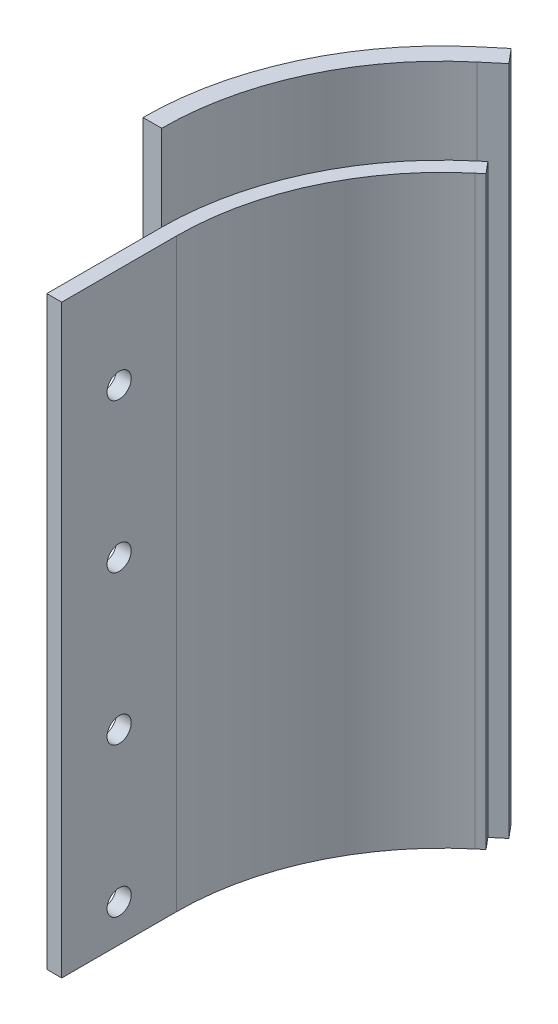
SolidWorks part; units mm, degrees
material "Custom Plastic"
ref_plane "Front Plane" through (0, 0, 0) normal (0, 0, 1) x (1, 0, 0)
ref_plane "Top Plane" through (0, 0, 0) normal (0, 1, 0) x (1, 0, 0)
ref_plane "Right Plane" through (0, 0, 0) normal (1, 0, 0) x (0, 0, -1)
sketch "Sketch1" plane through (0, 0, 0) normal (0, 1, 0) x (1, 0, 0)
  line L0 (0, 0) -> (77.7862, 0) construction
  line L1 (77.7862, 0) -> (77.7862, 50) construction
  line L2 (0, 0) -> (0, -10) construction
  line L3 (23.3154, 50) -> (-36.2723, 0) construction
  line L4 (10, 0) -> (-10, 0)
  line L5 (29.7433, 42.3396) -> (16.8875, 57.6604)
  arc A0 (0, 0) -> (23.3154, 50) centre (65.2704, 0) cw construction
  arc A1 (10, 0) -> (29.7433, 42.3396) centre (65.2704, 0) cw
  arc A2 (-10, 0) -> (16.8875, 57.6604) centre (65.2704, 0) cw
  circle A3 centre (0.7706, 10) radius 2.6
  circle A4 centre (6.1153, 27.5844) radius 2.6
  circle A5 centre (16.1503, 42.9818) radius 2.6
  circle A7 centre (30.0798, 54.9713) radius 2.6 [skipped]
  point P24 (65.2704, 0)
  dimension "D6" = 5.2
  dimension "D9" = 10
  dimension "D1" = 10
  dimension "D2" = 40
  dimension "D3" = 50
  dimension "D7" = 10
  dimension "D8" = 4
  dimension "D4" = 10
  dimension "D5" = 10
extrude "Boss-Extrude1" add sketch "Sketch1" along normal blind 20
sketch "Sketch2" plane through (0, 20, 0) normal (0, 1, 0) x (1, 0, 0)
  line L0 (16.8875, 57.6604) -> (29.7433, 42.3396)
  line L1 (16.8875, 57.6604) -> (21.5604, 61.5814)
  line L2 (29.7433, 42.3396) -> (34.4161, 46.2606)
  line L3 (21.5604, 61.5814) -> (34.4161, 46.2606)
  dimension "D1" = 6.1
extrude "Boss-Extrude2" add sketch "Sketch2" against normal up to surface (20 mm away) up to face at (0.7706, 0, -7.4)
sketch "Sketch3" plane through (0, 20, 0) normal (0, 1, 0) x (1, 0, 0)
  line L5 (21.5604, 61.5814) -> (16.8875, 57.6604) construction
  line L6 (18.3464, 65.4117) -> (13.6736, 61.4907)
  line L7 (18.3464, 65.4117) -> (13.6736, 61.4907)
  line L8 (21.5604, 61.5814) -> (16.8875, 57.6604)
  line L9 (-15, 0) -> (-10, 0)
  line L10 (18.3464, 65.4117) -> (21.5604, 61.5814)
  arc A4 (16.8875, 57.6604) -> (-10, 0) centre (65.2704, 0) ccw construction
  arc A5 (13.6736, 61.4907) -> (-15, 0) centre (65.2704, 0) ccw
  arc A6 (13.6736, 61.4907) -> (-15, 0) centre (65.2704, 0) ccw
  arc A7 (16.8875, 57.6604) -> (-10, 0) centre (65.2704, 0) ccw
  dimension "D1" = 5
extrude "Boss-Extrude3" add sketch "Sketch3" along normal blind 180 separate body
sketch "Sketch4" plane through (0, 20, 0) normal (0, 1, 0) x (1, 0, 0)
  line L4 (29.7433, 42.3396) -> (34.4161, 46.2606)
  line L5 (34.4161, 46.2606) -> (21.5604, 61.5814)
  line L6 (21.5604, 61.5814) -> (16.8875, 57.6604)
  line L7 (-10, 0) -> (10, 0)
  line L8 (29.7433, 42.3396) -> (34.4161, 46.2606)
  line L9 (34.4161, 46.2606) -> (21.5604, 61.5814)
  line L10 (21.5604, 61.5814) -> (16.8875, 57.6604)
  line L11 (-10, 0) -> (10, 0)
  arc A2 (29.7433, 42.3396) -> (10, 0) centre (65.2704, 0) ccw
  arc A3 (16.8875, 57.6604) -> (-10, 0) centre (65.2704, 0) ccw
  arc A4 (29.7433, 42.3396) -> (10, 0) centre (65.2704, 0) ccw
  arc A5 (16.8875, 57.6604) -> (-10, 0) centre (65.2704, 0) ccw
  dimension "D1" = 0
extrude "Cut-Extrude1" cut sketch "Sketch4" against normal through all
sketch "Sketch6" plane through (0, 200, 0) normal (0, 1, 0) x (1, 0, 0)
  line L0 (16.8875, 57.6604) -> (21.5604, 61.5814) construction
  line L1 (16.8875, 57.6604) -> (21.5604, 61.5814)
  line L2 (-10, 0) -> (-10, -30.7992)
  line L3 (-10, -30.7992) -> (-6, -30.7992)
  line L4 (-6, -30.7992) -> (-6, 0)
  line L5 (19.4587, 54.5963) -> (24.1315, 58.5173)
  line L6 (21.5604, 61.5814) -> (24.1315, 58.5173)
  arc A0 (16.8875, 57.6604) -> (-10, 0) centre (65.2704, 0) ccw construction
  arc A1 (16.8875, 57.6604) -> (-10, 0) centre (65.2704, 0) ccw
  arc A2 (19.4587, 54.5963) -> (-6, 0) centre (65.2704, 0) ccw
  dimension "D1" = 4
extrude "Boss-Extrude4" add sketch "Sketch6" against normal up to surface (157 mm away) from offset 23 up to face at (5.3767, 20, -42.0505) offset against normal yes
sketch "Sketch7" plane through (-10, 0, 0) normal (-1, 0, 0) x (0, 0, 1)
  line L0 (15.3996, 177) -> (15.3996, 20) construction
  line L1 (0, 177) -> (30.7992, 177) construction
  line L2 (30.7992, 20) -> (0, 20) construction
  circle A0 centre (15.3996, 30) radius 3.25
  circle A1 centre (15.3996, 70) radius 3.25
  circle A2 centre (15.3996, 110) radius 3.25
  circle A3 centre (15.3996, 150) radius 3.25
  dimension "D1" = 6.5
  dimension "D2" = 10
  dimension "D4" = 40
  dimension "D3" = 4
extrude "Cut-Extrude2" cut sketch "Sketch7" against normal through all
sketch "Sketch8" plane through (0, 200, 0) normal (0, 1, 0) x (1, 0, 0)
  line L4 (21.5604, 61.5814) -> (24.1315, 58.5173)
  line L5 (21.5604, 61.5814) -> (18.4962, 59.0103)
  line L6 (24.1315, 58.5173) -> (21.0674, 55.9461)
  line L7 (18.4962, 59.0103) -> (21.0674, 55.9461)
  dimension "D1" = 4
extrude "Cut-Extrude3" cut sketch "Sketch8" against normal through all
